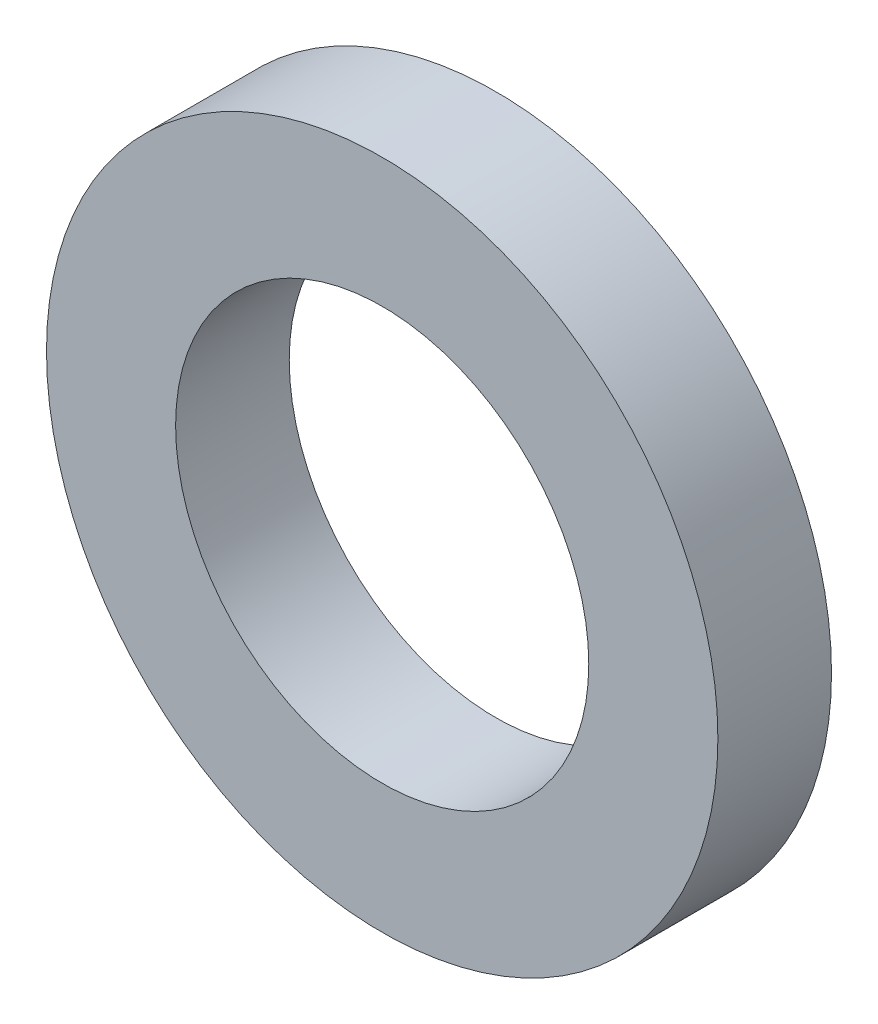
SolidWorks part; units mm, degrees
ref_plane "前视基准面" through (0, 0, 0) normal (0, 0, 1) x (1, 0, 0)
ref_plane "上视基准面" through (0, 0, 0) normal (0, 1, 0) x (1, 0, 0)
ref_plane "右视基准面" through (0, 0, 0) normal (1, 0, 0) x (0, 0, -1)
sketch "草图1" plane through (0, 0, 0) normal (0, 0, 1) x (1, 0, 0)
  circle A0 centre (0, 0) radius 2
  circle A1 centre (0, 0) radius 3.25
extrude "凸台-拉伸1" add sketch "草图1" along normal blind 1.1
